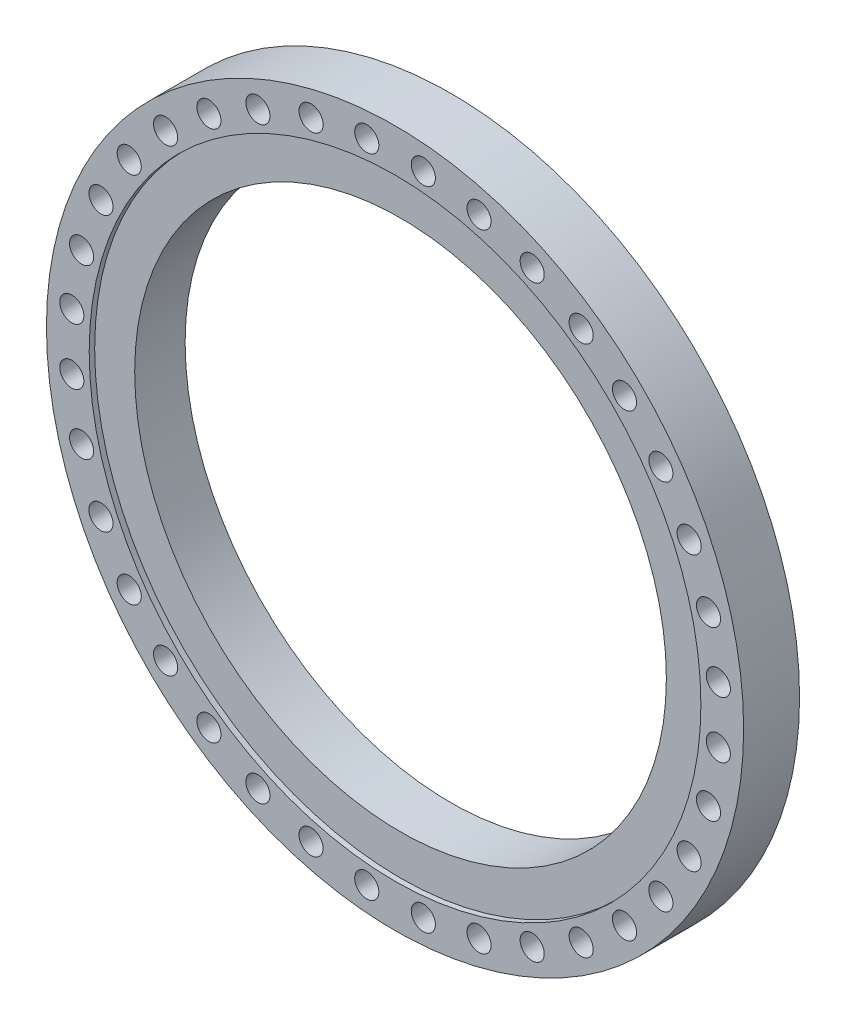
SolidWorks part; units mm, degrees
ref_plane "Front Plane" through (0, 0, 0) normal (0, 0, 1) x (1, 0, 0)
ref_plane "Top Plane" through (0, 0, 0) normal (0, 1, 0) x (1, 0, 0)
ref_plane "Right Plane" through (0, 0, 0) normal (1, 0, 0) x (0, 0, -1)
sketch "Sketch1" plane through (0, 0, 0) normal (1, 0, 0) x (0, 0, -1)
  line L0 (0, 0) -> (215.5415, 0) construction
  line L1 (0, 279) -> (0, 318)
  line L2 (0, 318) -> (51, 318)
  line L3 (51, 318) -> (51, 242.5)
  line L5 (2301, 254) -> (2301, 233.4)
  line L9 (0, 279) -> (5, 279)
  line L10 (5, 279) -> (5, 242.5)
  line L11 (5, 242.5) -> (51, 242.5)
  point P3 (0, 0)
  point P10 (51, 243.1156)
  dimension "D1" = 485
  dimension "D2" = 636
  dimension "D3" = 558
  dimension "D6" = 51
  dimension "D7" = 5
  dimension "D8" = 2250
revolve "Revolve3" add sketch "Sketch1" angle 360 about L0
sketch "Sketch10" plane through (0, 0, 0) normal (0, 0, 1) x (1, 0, 0)
  line L0 (0, 0) -> (0, 534.1537) construction
  line L1 (0, 0) -> (-48.1006, 549.7918) construction
  line L2 (0, 0) -> (-125.8916, 469.8338) construction
  circle A0 centre (0, 0) radius 296 construction
  circle A1 centre (-25.7981, 294.8736) radius 11
  circle A2 centre (25.7981, 294.8736) radius 11
  circle A3 centre (76.6104, 285.914) radius 11
  circle A4 centre (125.095, 268.2671) radius 11
  circle A5 centre (169.7786, 242.469) radius 11
  circle A6 centre (209.3036, 209.3036) radius 11
  circle A7 centre (242.469, 169.7786) radius 11
  circle A8 centre (268.2671, 125.095) radius 11
  circle A9 centre (285.914, 76.6104) radius 11
  circle A10 centre (294.8736, 25.7981) radius 11
  circle A11 centre (294.8736, -25.7981) radius 11
  circle A12 centre (285.914, -76.6104) radius 11
  circle A13 centre (268.2671, -125.095) radius 11
  circle A14 centre (242.469, -169.7786) radius 11
  circle A15 centre (209.3036, -209.3036) radius 11
  circle A16 centre (169.7786, -242.469) radius 11
  circle A17 centre (125.095, -268.2671) radius 11
  circle A18 centre (76.6104, -285.914) radius 11
  circle A19 centre (25.7981, -294.8736) radius 11
  circle A20 centre (-25.7981, -294.8736) radius 11
  circle A21 centre (-76.6104, -285.914) radius 11
  circle A22 centre (-125.095, -268.2671) radius 11
  circle A23 centre (-169.7786, -242.469) radius 11
  circle A24 centre (-209.3036, -209.3036) radius 11
  circle A25 centre (-242.469, -169.7786) radius 11
  circle A26 centre (-268.2671, -125.095) radius 11
  circle A27 centre (-285.914, -76.6104) radius 11
  circle A28 centre (-294.8736, -25.7981) radius 11
  circle A29 centre (-294.8736, 25.7981) radius 11
  circle A30 centre (-285.914, 76.6104) radius 11
  circle A31 centre (-268.2671, 125.095) radius 11
  circle A32 centre (-242.469, 169.7786) radius 11
  circle A33 centre (-209.3036, 209.3036) radius 11
  circle A34 centre (-169.7786, 242.469) radius 11
  circle A35 centre (-125.095, 268.2671) radius 11
  circle A36 centre (-76.6104, 285.914) radius 11
  point P8 (0, 0)
  point P81 (0, 0)
  dimension "D1" = 592
  dimension "D2" = 22
  dimension "D3" = 5
  dimension "D4" = 10
  dimension "D5" = 36
extrude "Cut-Extrude5" cut sketch "Sketch10" against normal blind 463
